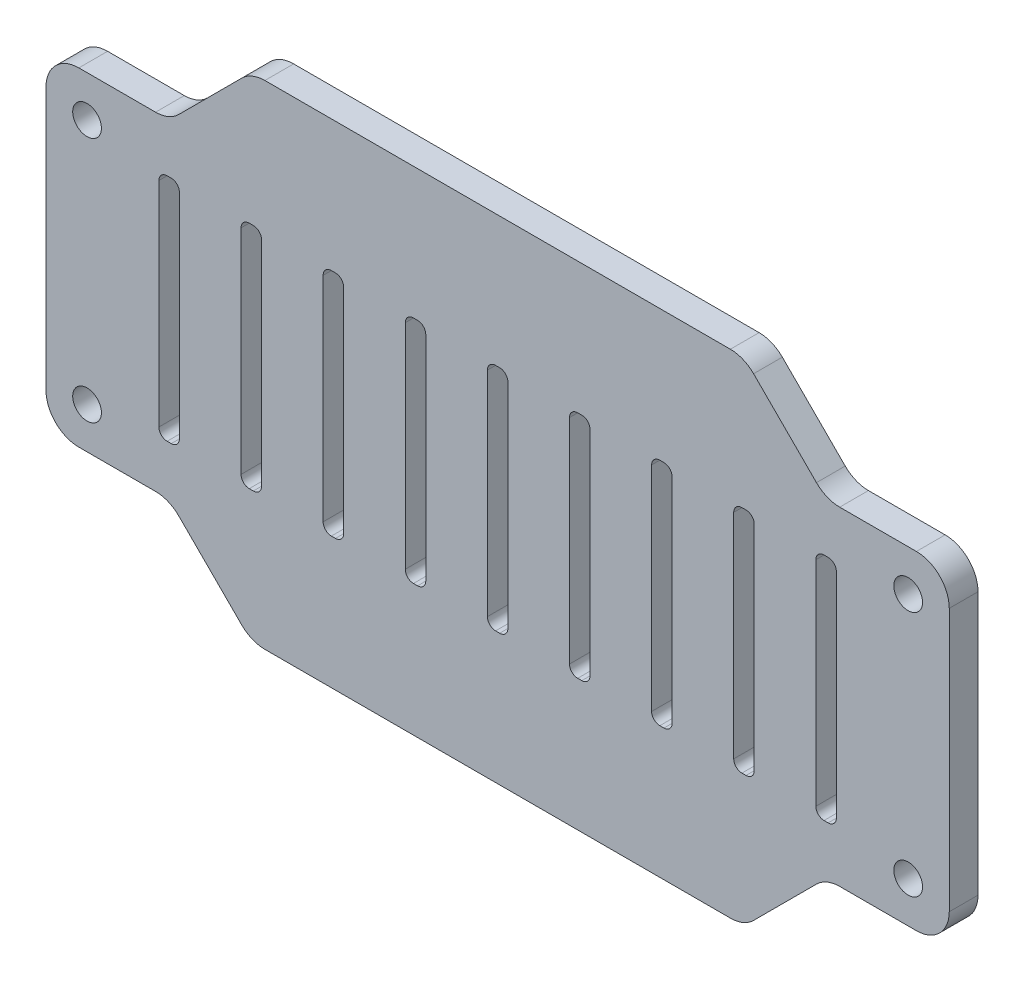
SolidWorks part; units mm, degrees
ref_plane "Front Plane" through (0, 0, 0) normal (0, 0, 1) x (1, 0, 0)
ref_plane "Top Plane" through (0, 0, 0) normal (0, 1, 0) x (1, 0, 0)
ref_plane "Right Plane" through (0, 0, 0) normal (1, 0, 0) x (0, 0, -1)
sketch "Sketch1" plane through (0, 0, 0) normal (0, 0, 1) x (1, 0, 0)
  line L0 (-55, 20) -> (-40, 20)
  line L1 (55, 20) -> (-55, 20) construction
  line L2 (55, 20) -> (55, -20)
  line L3 (55, -20) -> (-55, -20) construction
  line L4 (-55, 20) -> (-55, -20)
  line L5 (55, 20) -> (-55, -20) construction
  line L6 (55, -20) -> (-55, 20) construction
  line L7 (-30, 30) -> (30, 30)
  line L8 (-30, 30) -> (-30, -30) construction
  line L9 (-30, -30) -> (30, -30)
  line L10 (30, 30) -> (30, -30) construction
  line L11 (-30, 30) -> (30, -30) construction
  line L12 (-30, -30) -> (30, 30) construction
  line L13 (-40, 20) -> (-30, 30)
  line L14 (-40, 20) -> (-40, -20) construction
  line L15 (-40, -20) -> (-30, -30)
  line L16 (-55, -20) -> (-40, -20)
  line L17 (30, -30) -> (40, -20)
  line L18 (40, -20) -> (55, -20)
  line L19 (40, -20) -> (40, 20) construction
  line L20 (40, 20) -> (30, 30)
  line L21 (40, 20) -> (55, 20)
  point P0 (0, 0)
  point P6 (0, 0)
  point P16 (0, 0)
  point P17 (0, 0)
  dimension "D1" = 40
  dimension "D2" = 110
  dimension "D3" = 60
  dimension "D4" = 45
  dimension "D5" = 60
extrude "Boss-Extrude1" add sketch "Sketch1" along normal blind 3.5
fillet "Fillet1" radius 4 12 edges at (-40, 20, 1.75) (-30, 30, 1.75) (30, 30, 1.75) (40, 20, 1.75) (55, 20, 1.75) (55, -20, 1.75) (40, -20, 1.75) (30, -30, 1.75) (-30, -30, 1.75) (-40, -20, 1.75) (-55, -20, 1.75) (-55, 20, 1.75)
sketch "Sketch2" plane through (0, 0, 3.5) normal (0, 0, 1) x (1, 0, 0)
  line L1 (-50, 15) -> (50, 15) construction
  line L2 (-50, 15) -> (-50, -15) construction
  line L3 (-50, -15) -> (50, -15) construction
  line L4 (50, 15) -> (50, -15) construction
  line L5 (-50, 15) -> (50, -15) construction
  line L6 (-50, -15) -> (50, 15) construction
  circle A0 centre (-50, 15) radius 1.75
  circle A1 centre (-50, -15) radius 1.75
  circle A2 centre (50, -15) radius 1.75
  circle A3 centre (50, 15) radius 1.75
  point P0 (0, 0)
  dimension "D1" = 3.5
  dimension "D2" = 30
  dimension "D3" = 100
extrude "Cut-Extrude1" cut sketch "Sketch2" against normal through all
sketch "Sketch3" plane through (0, 0, 3.5) normal (0, 0, 1) x (1, 0, 0)
  line L1 (-0.25, 14) -> (0.25, 14)
  line L2 (-1.25, 13) -> (-1.25, -13)
  line L3 (-0.25, -14) -> (0.25, -14)
  line L4 (1.25, 13) -> (1.25, -13)
  line L5 (-1.25, 14) -> (1.25, -14) construction
  line L6 (-1.25, -14) -> (1.25, 14) construction
  arc A0 (0.25, -14) -> (1.25, -13) centre (0.25, -13) ccw
  arc A1 (-1.25, -13) -> (-0.25, -14) centre (-0.25, -13) ccw
  arc A2 (0.25, 14) -> (1.25, 13) centre (0.25, 13) cw
  arc A3 (-0.25, 14) -> (-1.25, 13) centre (-0.25, 13) ccw
  point P0 (0, 0)
  dimension "D3" = 1
  dimension "D1" = 2.5
  dimension "D2" = 28
extrude "Cut-Extrude2" cut sketch "Sketch3" against normal through all
pattern_linear "LPattern1" count 5 spacing 10 along (-1, 0, 0) count 5 spacing 10 along (1, 0, 0) of "Cut-Extrude2"
